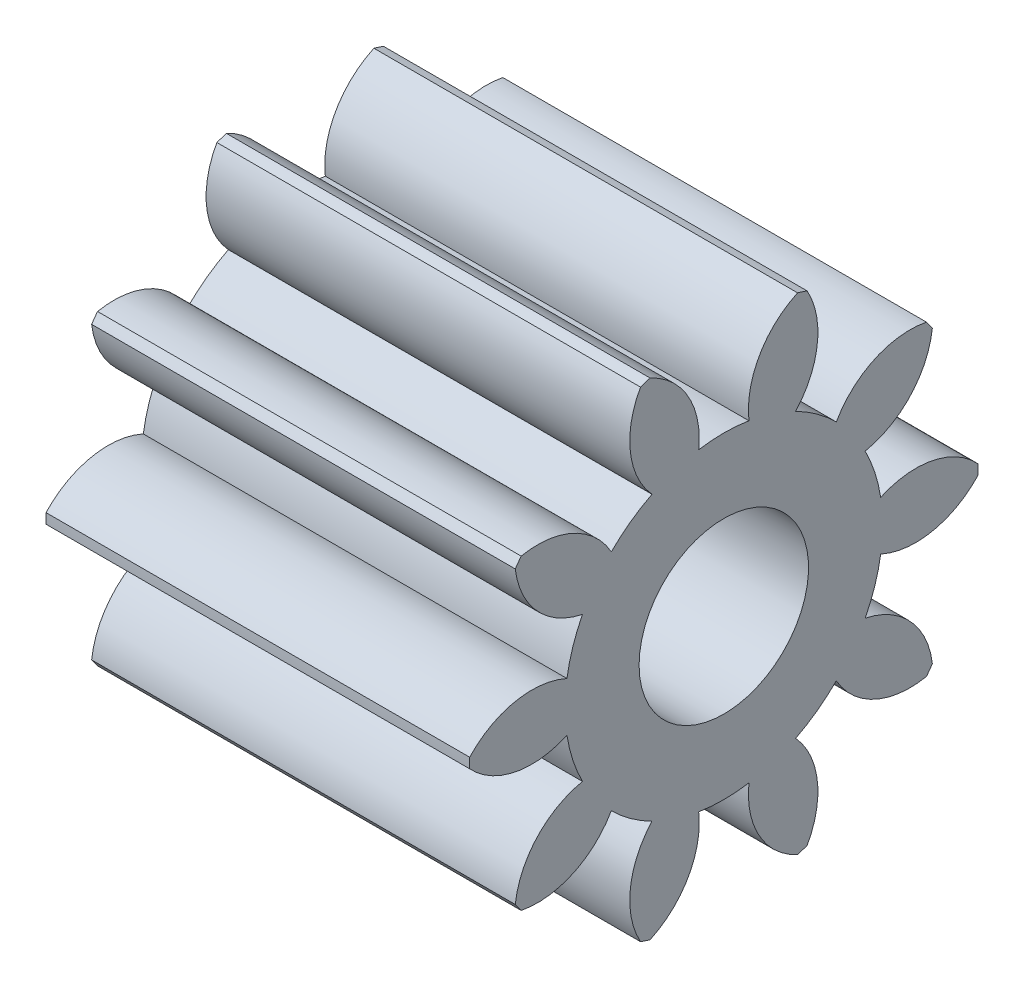
SolidWorks part; units mm, degrees
ref_plane "Plane1" through (0, 0, 0) normal (0, 0, 1) x (1, 0, 0)
ref_plane "Plane2" through (0, 0, 0) normal (0, 1, 0) x (1, 0, 0)
ref_plane "Plane3" through (0, 0, 0) normal (1, 0, 0) x (0, 0, -1)
other "Configuration Table"
sketch "HoldingSke" plane through (0, 0, 0) normal (0, 1, 0) x (1, 0, 0)
  line L0 (0, 0) -> (1.9696, -0.3473)
  line L1 (-15, 0) -> (100, 0) construction
  line L2 (0, 0) -> (-2.1039, 2.3779)
  line L3 (0, 0) -> (-11.863, 4.5341)
  line L4 (0, 0) -> (8.5048, 1.4996)
  line L5 (0, 0) -> (-46.8476, -17.4728)
  line L6 (0, 0) -> (-4.1448, -2.7965)
  line L7 (-2.1039, 2.3779) -> (8.6586, 51.206)
  line L8 (-76.2, 54.61) -> (-76, 54.61)
  line L9 (-71.009, 38.7566) -> (-53.1078, 45.2721)
  line L10 (-76.2, 71.12) -> (104.1128, 71.12)
  line L11 (0, 0) -> (-5, 0)
  line L12 (-76.2, 101.6) -> (-76.181, 101.6)
  line L13 (24.9733, 27.94) -> (52.9518, 28.4284)
  line L14 (24.9733, 27.94) -> (24.9743, 27.94)
  line L15 (24.9733, 27.94) -> (100.4006, 29.5858)
  line L16 (-63.627, -0.5) -> (-12.827, -0.5)
  circle A0 centre (0, 0) radius 0.75
  circle A1 centre (0, 0) radius 1.874
  circle A2 centre (0, 0) radius 37.5
  circle A3 centre (0, 0) radius 0.75
  dimension "MHD" = 3.748
  dimension "Hub_dia" = 75
  dimension "Bore" = 1.5
  dimension "MBD" = 1.5
  dimension "Num_teeth" = 10
  dimension "Pitch" = 2
  dimension "Overall_len" = 50
  dimension "Show_teeth" = 10
  dimension "Thickness" = 5
  dimension "OAL" = 50.0002
  dimension "T_dim" = 0.2
  dimension "Ap" = 20
  dimension "H" = 19.05
  dimension "Pitch_radius" = 180.3128
  dimension "Width" = 5
  dimension "Backlash" = 0.019
  dimension "Addendum_fac" = 1
  dimension "Dedendum_fac" = 1.25
  dimension "Clearance_fac" = 0.25
  dimension "Dedendum_add" = 0.001
  dimension "Module" = 0.5
sketch "BasProSke" plane through (0, 0, 0) normal (0, 1, 0) x (1, 0, 0)
  line L0 (-10, 0) -> (60, 0) construction
  line L1 (0, 0) -> (0, 3)
  line L2 (0, 0) -> (5, 0)
  line L3 (5, 0) -> (5, 3)
  line L4 (5, 3) -> (0, 3)
  dimension "Thickness" = 5
  dimension "Diameter" = 6
revolve "Base-Revolve" add sketch "BasProSke" angle 360 about L0
sketch "TooCutSke" plane through (0, 0, 0) normal (1, 0, 0) x (0, 0, -1)
  line L1 (0, 0) -> (0, 107) construction
  line L2 (0, 0) -> (-0.4243, 2.4637) construction
  line L3 (0, 0) -> (-1.5292, 4.7063) construction
  line L4 (-0.4243, 2.4637) -> (-0.7646, 2.3532) construction
  arc A0 (0.2964, 1.8504) -> (-0.2964, 1.8504) centre (0, 0) ccw
  arc A1 (0.9059, 2.8866) -> (-0.9059, 2.8866) centre (0, 0) ccw
  circle A2 centre (0, 0) radius 2.5 construction
  circle A3 centre (0, 0) radius 2.3492 construction
  arc A4 (-0.2964, 1.8504) -> (-0.9059, 2.8866) centre (-1.2901, 1.9633) ccw
  arc A5 (0.9059, 2.8866) -> (0.2964, 1.8504) centre (1.2901, 1.9633) ccw
  dimension "Root_dia" = 3.748
  dimension "Overcut_dia" = 6.0508
  dimension "Pitch_dia" = 5
  dimension "Base_dia" = 4.6985
  dimension "Flank_rad" = 1
  dimension "Half_ang" = 18
  dimension "Half_CT" = 0.3578
extrude "ToothCut" cut sketch "TooCutSke" along normal through all
fillet "Breaks" [suppressed] radius 0.01
fillet "RootFillets" [suppressed] radius 0.126
pattern_circular "TeethCuts" count 10 every 36 about axis through (-10, 0, 0) along (1, 0, 0) of "ToothCut", "RootFillets", "Breaks"
sketch "HubNeaOneSke" plane through (0, 0, 0) normal (-1, 0, 0) x (0, 0, 1)
  circle A0 centre (0, 0) radius 1.874
  dimension "Diameter" = 3.748
extrude "HubNearOne" [suppressed] add sketch "HubNeaOneSke" along normal blind 45.0002
sketch "HubNeaBotSke" plane through (0, 0, 0) normal (-1, 0, 0) x (0, 0, 1)
  circle A0 centre (0, 0) radius 1.874
  dimension "Diameter" = 3.748
extrude "HubNearBoth" [suppressed] add sketch "HubNeaBotSke" along normal blind 22.5001
ref_plane "FarPln" through (5, 0, 0) normal (1, 0, 0) x (0, 0, -1)
sketch "HubFarSke" plane through (5, 0, 0) normal (1, 0, 0) x (0, 0, -1)
  circle A0 centre (0, 0) radius 1.874
  dimension "Diameter" = 3.748
extrude "HubFar" [suppressed] add sketch "HubFarSke" along normal blind 22.5001
sketch "BorSke" plane through (0, 0, 0) normal (1, 0, 0) x (0, 0, -1)
  circle A0 centre (0, 0) radius 1
  dimension "Diameter" = 2
extrude "Bore" cut sketch "BorSke" along normal mid plane 100.0004
sketch "KeySke" plane through (0, 0, 0) normal (1, 0, 0) x (0, 0, -1)
  line L0 (-0.3, 0) -> (-0.3, 0.95)
  line L1 (-0.3, 0.95) -> (0.3, 0.95)
  line L2 (0.3, 0.95) -> (0.3, 0)
  line L3 (0, 0) -> (0, 34) construction
  line L4 (-0.3, 0) -> (0.3, 0)
  dimension "Offset" = 0.95
  dimension "Width" = 0.6
extrude "Keyway" [suppressed] cut sketch "KeySke" along normal mid plane 100.0004
pattern_circular "Keyway2" [suppressed] count 2 every 90 about axis through (-10, 0, 0) along (1, 0, 0)
equation "' \"Module@HoldingSke\" = 6.35"
equation "' \"Num_teeth@HoldingSke\" = 12"
equation "' \"Ap@HoldingSke\" =  20"
equation "' \"Ap@HoldingSke\" = 20"
equation "' \"Width@HoldingSke\" = 0.5 * 25.4"
equation "' \"Hub_dia@HoldingSke\"= 1 * 25.4"
equation "' \"Hub_dia@HoldingSke\" = 1 * 25.4"
equation "' \"Overall_len@HoldingSke\" = 1.0 * 25.4"
equation "' \"Bore@HoldingSke\" = 0.75 * 25.4"
equation "' \"T_dim@HoldingSke\" = 0.1 * 25.4"
equation "' \"Width@KeySke\" = 0.25 * 25.4"
equation "' \"Show_teeth@HoldingSke\" = 13"
equation "' \"Backlash@HoldingSke\" = 0.009 * 25.4"
equation "' \"Addendum_fac@HoldingSke\" = 1.0"
equation "' \"Dedendum_fac@HoldingSke\" = 1.25"
equation "' \"Dedendum_add@HoldingSke\" = 0.00005 * 25.4"
equation "' \"Clearance_fac@HoldingSke\" = 0.25"
equation "\"Pitch@HoldingSke\" = 1 / \"Module@HoldingSke\""
equation "\"Overcut_dia@TooCutSke\" = (\"Num_teeth@HoldingSke\" + 2 * \"Addendum_fac@HoldingSke\") / \"Pitch@HoldingSke\" + 0.002 * 25.4"
equation "\"Pitch_dia@TooCutSke\" = \"Num_teeth@HoldingSke\" / \"Pitch@HoldingSke\""
equation "\"Base_dia@TooCutSke\" = \"Num_teeth@HoldingSke\" / \"Pitch@HoldingSke\" * cos((\"Ap@HoldingSke\"  * 3.14159265 / 180))"
equation "\"Root_dia@TooCutSke\" = (\"Num_teeth@HoldingSke\" + 2) / \"Pitch@HoldingSke\" - 2 * (\"Addendum_fac@HoldingSke\" + \"Dedendum_fac@HoldingSke\") / \"Pitch@HoldingSke\" - \"Dedendum_add@HoldingSke\" * 2"
equation "\"Half_ang@TooCutSke\" = 180 / \"Num_teeth@HoldingSke\""
equation "\"Half_CT@TooCutSke\" = \"Num_teeth@HoldingSke\" / \"Pitch@HoldingSke\" * sin((3.14159265 / 2 / \"Num_teeth@HoldingSke\")) / 2 - 7 * \"Backlash@HoldingSke\" / 4"
equation "\"Flank_rad@TooCutSke\" = \"Num_teeth@HoldingSke\" / \"Pitch@HoldingSke\" / 5"
equation "\"Radius@RootFillets\" = \"Clearance_fac@HoldingSke\" / \"Pitch@HoldingSke\" + \"Dedendum_add@HoldingSke\""
equation "\"Break_rad@Breaks\" = 0.02 / \"Pitch@HoldingSke\""
equation "\"Thickness@HoldingSke\" = \"Width@HoldingSke\""
equation "\"OAL@HoldingSke\" = \"Thickness@HoldingSke\""
equation "\"MHD@HoldingSke\" = (\"Num_teeth@HoldingSke\" + 2) / \"Pitch@HoldingSke\" - 2 * (\"Addendum_fac@HoldingSke\" + \"Dedendum_fac@HoldingSke\")  / \"Pitch@HoldingSke\" - \"Dedendum_add@HoldingSke\" * 2"
equation "\"MBD@HoldingSke\" = (\"Num_teeth@HoldingSke\" + 2) / \"Pitch@HoldingSke\" - 2 * (\"Addendum_fac@HoldingSke\" + \"Dedendum_fac@HoldingSke\")  / \"Pitch@HoldingSke\" - \"Dedendum_add@HoldingSke\" * 2 - 0.002 * 25.4"
equation "\"MHD@HoldingSke\" = ((sgn( \"MHD@HoldingSke\" - \"Hub_dia@HoldingSke\" )-1)*( \"MHD@HoldingSke\" - \"Hub_dia@HoldingSke\" ))/-2+ \"Hub_dia@HoldingSke\""
equation "\"MBD@HoldingSke\" = ((sgn( \"MBD@HoldingSke\" - \"Bore@HoldingSke\" )-1)*( \"MBD@HoldingSke\" - \"Bore@HoldingSke\" ))/-2+ \"Bore@HoldingSke\""
equation "\"OAL@HoldingSke\" = ((sgn( \"OAL@HoldingSke\" - \"Overall_len@HoldingSke\" )+1)*( \"OAL@HoldingSke\" - \"Overall_len@HoldingSke\" ))/2 + \"Overall_len@HoldingSke\" + 0.000002 * 25.4"
equation "\"Num_teeth@TeethCuts\" = int( \"Show_teeth@HoldingSke\" ) + 1"
equation "\"Num_teeth@TeethCuts\" = ((sgn( \"Num_teeth@TeethCuts\" - \"Num_teeth@HoldingSke\" )-1)*( \"Num_teeth@TeethCuts\" - \"Num_teeth@HoldingSke\" ))/-2+ \"Num_teeth@HoldingSke\""
equation "\"Num_teeth@TeethCuts\" = ((sgn( \"Num_teeth@TeethCuts\" - 2.0)+1)*( \"Num_teeth@TeethCuts\" - 2.0))/2 +2.0"
equation "\"Angle@TeethCuts\" = 360.0 / \"Num_teeth@HoldingSke\""
equation "\"Diameter@BasProSke\" = (\"Num_teeth@HoldingSke\" + 2 * \"Addendum_fac@HoldingSke\") / \"Pitch@HoldingSke\""
equation "\"Thickness@BasProSke\"  = \"Thickness@HoldingSke\""
equation "' \"Fillet_rad@BasProSke\" =  \"Thickness@HoldingSke\" * 0.05"
equation "' \"Fillet_rad@BasProSke\" = \"Thickness@HoldingSke\" * 0.05"
equation "\"MHD@HoldingSke\" = ((sgn( \"MHD@HoldingSke\" - \"Root_dia@TooCutSke\" )-1)*( \"MHD@HoldingSke\" - \"Root_dia@TooCutSke\" ))/-2+ \"Root_dia@TooCutSke\""
equation "\"Diameter@HubNeaOneSke\" = \"MHD@HoldingSke\""
equation "\"Length@HubNearOne\" = \"OAL@HoldingSke\" - \"Thickness@BasProSke\""
equation "\"Diameter@HubNeaBotSke\" = \"MHD@HoldingSke\""
equation "\"Length@HubNearBoth\" = ( \"OAL@HoldingSke\" - \"Thickness@BasProSke\" ) / 2.0"
equation "\"Thickness@FarPln\" = \"Thickness@BasProSke\""
equation "\"Diameter@HubFarSke\" = \"MHD@HoldingSke\""
equation "\"Length@HubFar\" = ( \"OAL@HoldingSke\" - \"Thickness@BasProSke\" ) / 2.0"
equation "\"D1@Bore\"= \"OAL@HoldingSke\" * 2.0"
equation "\"D1@Keyway\" = \"OAL@HoldingSke\" * 2.0"
equation "\"Offset@KeySke\" = \"T_dim@HoldingSke\" + \"MBD@HoldingSke\" / 2.0"
